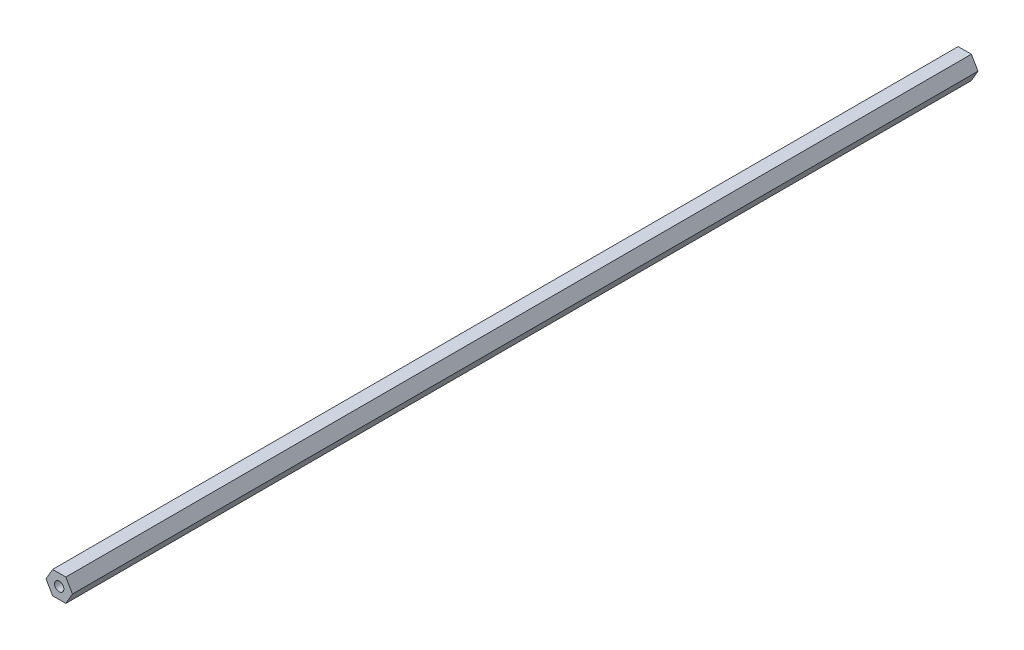
SolidWorks part; units mm, degrees
material "6061 Alloy"
ref_plane "Front Plane" through (0, 0, 0) normal (0, 0, 1) x (1, 0, 0)
ref_plane "Top Plane" through (0, 0, 0) normal (0, 1, 0) x (1, 0, 0)
ref_plane "Right Plane" through (0, 0, 0) normal (1, 0, 0) x (0, 0, -1)
sketch "Sketch 1" plane through (0, 0, 0) normal (0, 0, 1) x (1, 0, 0)
  line L1 (7.3323, 0) -> (3.6662, 6.35)
  line L2 (3.6662, 6.35) -> (-3.6662, 6.35)
  line L3 (-3.6662, 6.35) -> (-7.3323, 0)
  line L4 (-7.3323, 0) -> (-3.6662, -6.35)
  line L5 (-3.6662, -6.35) -> (3.6662, -6.35)
  line L6 (3.6662, -6.35) -> (7.3323, 0)
  circle A0 centre (0, 0) radius 6.35 construction
  dimension "D1" = 12.7
extrude "Boss-Extrude1" add sketch "Sketch 1" along normal blind 502.3485
sketch "Sketch1" plane through (0, 0, 502.3485) normal (0, 0, 1) x (1, 0, 0)
  circle A0 centre (0, 0) radius 2.5797
  dimension "D1" = 5.1594
extrude "Cut-Extrude1" cut sketch "Sketch1" against normal through all
